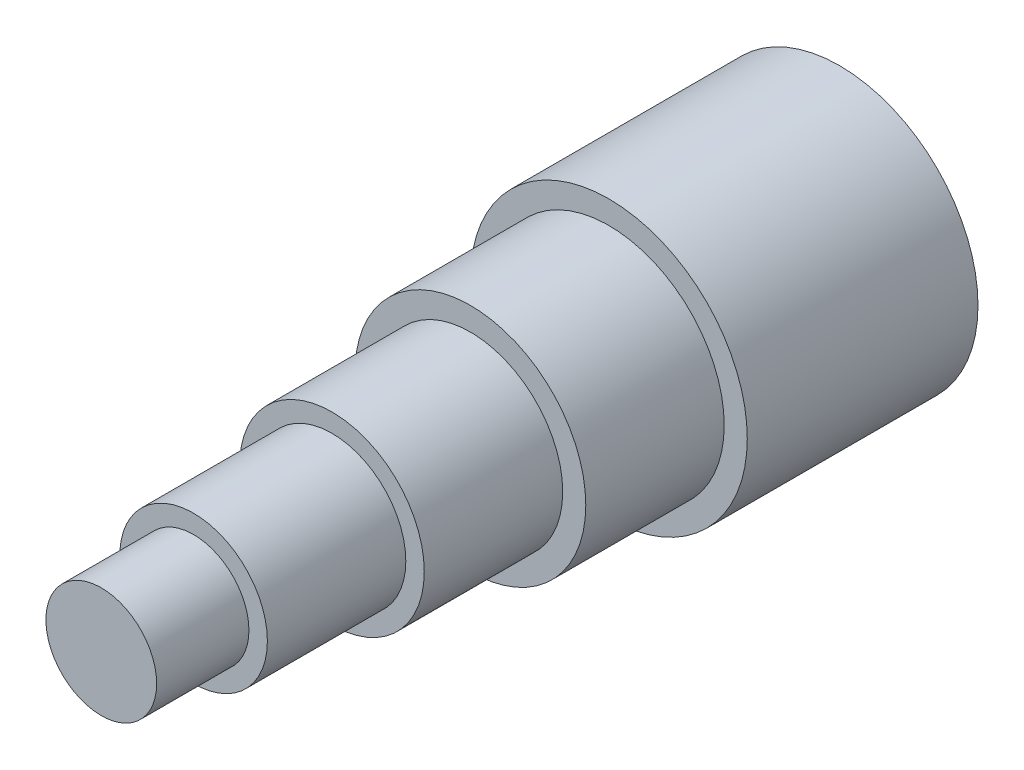
SolidWorks part; units mm, degrees
ref_plane "Front Plane" through (0, 0, 0) normal (0, 0, 1) x (1, 0, 0)
ref_plane "Top Plane" through (0, 0, 0) normal (0, 1, 0) x (1, 0, 0)
ref_plane "Right Plane" through (0, 0, 0) normal (1, 0, 0) x (0, 0, -1)
sketch "Sketch2" plane through (0, 0, 0) normal (0, 0, 1) x (1, 0, 0)
  circle A0 centre (0, 0) radius 15
  dimension "D1" = 30
extrude "Boss-Extrude1" add sketch "Sketch2" along normal mid plane 80 contours A0
sketch "Sketch3" plane through (0, 0, 40) normal (0, 0, 1) x (1, 0, 0)
  circle A0 centre (0, 0) radius 12.5
  circle M2 centre (0, 0) radius 15
  dimension "D1" = 25
extrude "Cut-Extrude1" cut sketch "Sketch3" against normal blind 55 contours A0 M2
sketch "Sketch4" plane through (0, 0, 40) normal (0, 0, 1) x (1, 0, 0)
  circle A0 centre (0, 0) radius 10
  circle M2 centre (0, 0) radius 12.5
  dimension "D1" = 20
extrude "Cut-Extrude2" cut sketch "Sketch4" against normal blind 40 contours A0 M2
sketch "Sketch5" plane through (0, 0, 40) normal (0, 0, 1) x (1, 0, 0)
  circle A0 centre (0, 0) radius 8
  circle M2 centre (0, 0) radius 10
  dimension "D1" = 16
extrude "Cut-Extrude3" cut sketch "Sketch5" against normal blind 25 contours A0 M2
sketch "Sketch6" plane through (0, 0, 40) normal (0, 0, 1) x (1, 0, 0)
  circle A0 centre (0, 0) radius 6
  circle M2 centre (0, 0) radius 8
  dimension "D1" = 12
extrude "Cut-Extrude4" cut sketch "Sketch6" against normal blind 10 contours A0 M2
